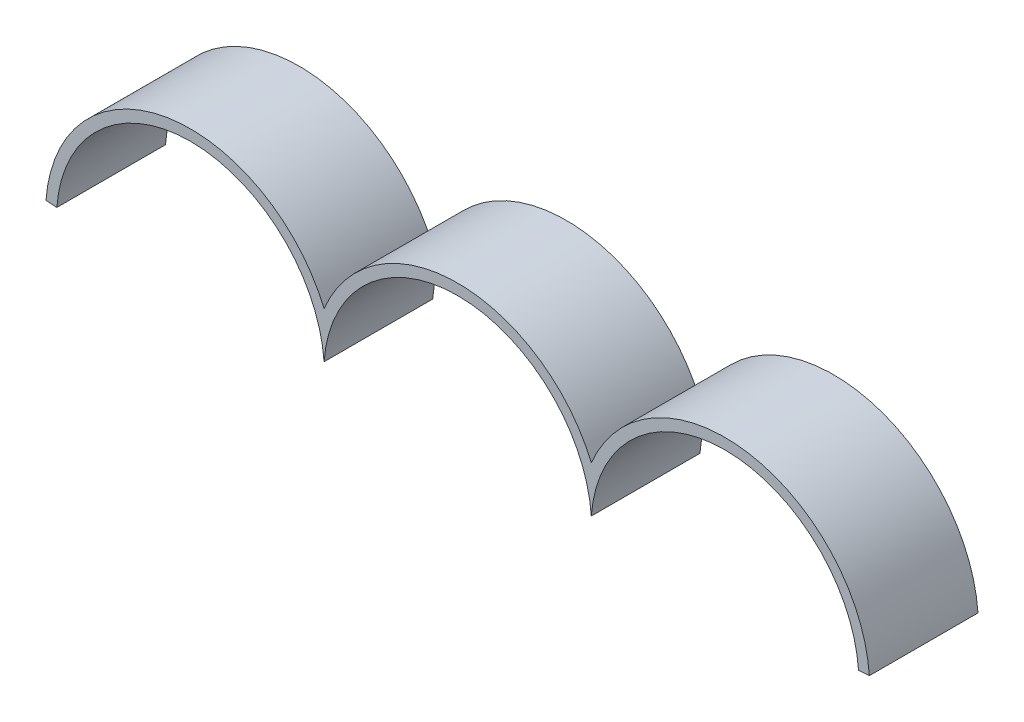
SolidWorks part; units mm, degrees
ref_plane "Plan de face" through (0, 0, 0) normal (0, 0, 1) x (1, 0, 0)
ref_plane "Plan de dessus" through (0, 0, 0) normal (0, 1, 0) x (1, 0, 0)
ref_plane "Plan de droite" through (0, 0, 0) normal (1, 0, 0) x (0, 0, -1)
sketch "Esquisse1" plane through (0, 0, 0) normal (0, 0, 1) x (1, 0, 0)
  line L0 (-76.7914, 0.2207) -> (-73.7995, 0)
  line L1 (150.591, 0.2207) -> (147.5991, 0)
  arc A0 (0, 0) -> (73.7995, 0) centre (36.8998, -2.7216) cw
  arc A1 (73.7995, 0) -> (147.5991, 0) centre (110.6993, -2.7216) cw
  arc A2 (0, 0) -> (-73.7995, 0) centre (-36.8998, -2.7216) ccw
  arc A3 (73.7995, 12.7189) -> (150.591, 0.2207) centre (110.6993, -2.7216) cw
  arc A4 (0, 12.7189) -> (73.7995, 12.7189) centre (36.8998, -2.7216) cw
  arc A5 (0, 12.7189) -> (-76.7914, 0.2207) centre (-36.8998, -2.7216) ccw
  dimension "D1" = 37
  dimension "D2" = 37
  dimension "D3" = 37
  dimension "D4" = 3
extrude "Boss.-Extru.1" add sketch "Esquisse1" along normal blind 30
